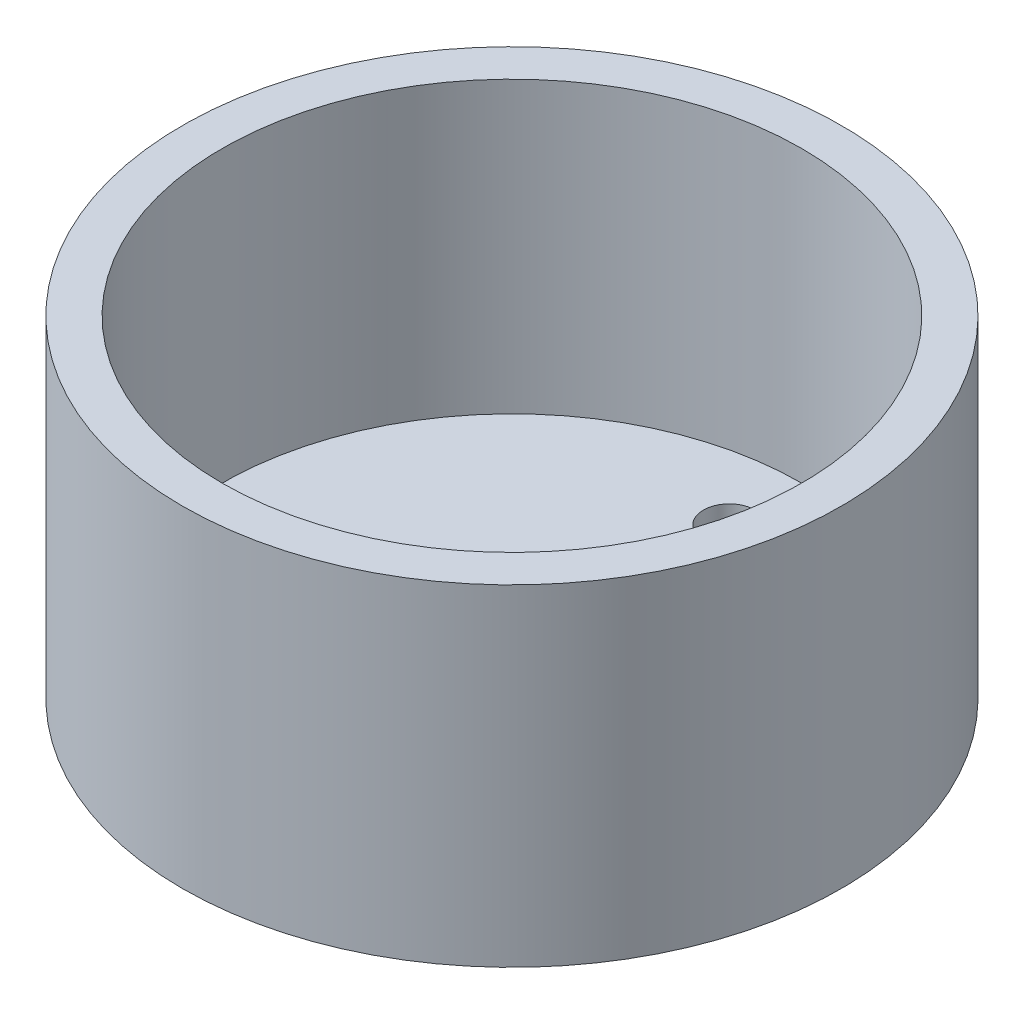
SolidWorks part; units mm, degrees
ref_plane "Front Plane" through (0, 0, 0) normal (0, 0, 1) x (1, 0, 0)
ref_plane "Top Plane" through (0, 0, 0) normal (0, 1, 0) x (1, 0, 0)
ref_plane "Right Plane" through (0, 0, 0) normal (1, 0, 0) x (0, 0, -1)
sketch "Sketch1" plane through (0, 0, 0) normal (0, 1, 0) x (1, 0, 0)
  circle A0 centre (0, 0) radius 50.546
extrude "Boss-Extrude1" add sketch "Sketch1" along normal blind 50.8
sketch "Sketch2" plane through (0, 50.8, 0) normal (0, 1, 0) x (1, 0, 0)
  circle A0 centre (0, 0) radius 44.45
extrude "Cut-Extrude1" cut sketch "Sketch2" against normal blind 44.45
sketch "Sketch3" plane through (0, 0, 0) normal (0, -1, 0) x (1, 0, 0)
  line L0 (0, 33.3375) -> (0, -33.3375)
  circle A0 centre (0, 33.3375) radius 3.9688
  circle A1 centre (0, -33.3375) radius 3.9688
  point P5 (0, 0)
  dimension "D2" = 7.9375
  dimension "D1" = 66.675
extrude "Cut-Extrude2" cut sketch "Sketch3" against normal blind 44.45
